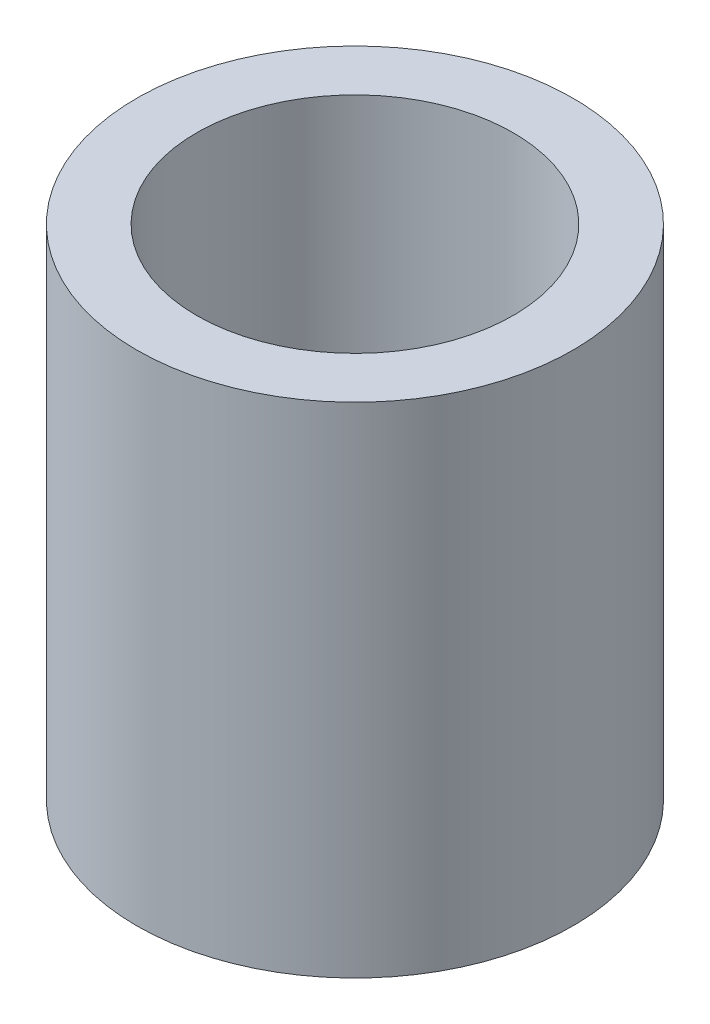
SolidWorks part; units mm, degrees
ref_plane "Front Plane" through (0, 0, 0) normal (0, 0, 1) x (1, 0, 0)
ref_plane "Top Plane" through (0, 0, 0) normal (0, 1, 0) x (1, 0, 0)
ref_plane "Right Plane" through (0, 0, 0) normal (1, 0, 0) x (0, 0, -1)
sketch "Sketch1" plane through (0, 0, 0) normal (0, 1, 0) x (1, 0, 0)
  circle A0 centre (0, 0) radius 3.5
  circle A1 centre (0, 0) radius 2.54
  dimension "D1" = 7
  dimension "D2" = 5.08
extrude "Boss-Extrude1" add sketch "Sketch1" along normal mid plane 8
